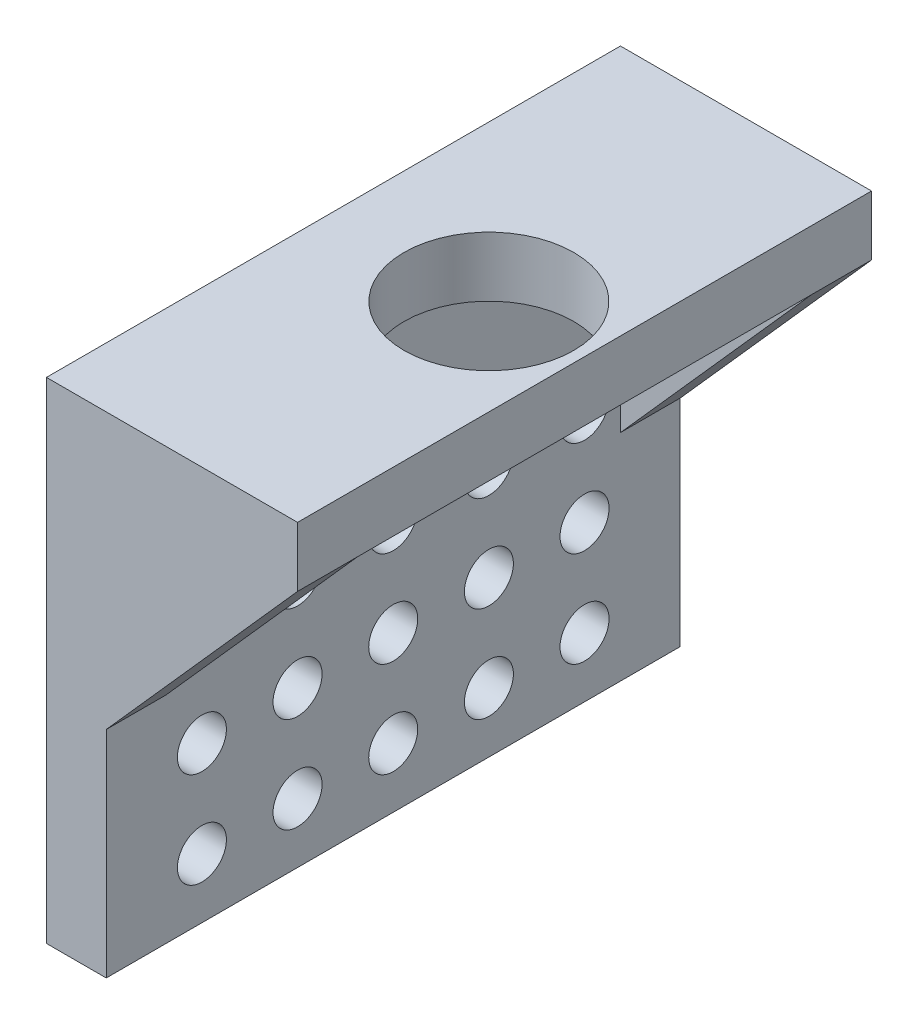
SolidWorks part; units mm, degrees
material "PMMA"
ref_plane "Front Plane" through (0, 0, 0) normal (0, 0, 1) x (1, 0, 0)
ref_plane "Top Plane" through (0, 0, 0) normal (0, 1, 0) x (1, 0, 0)
ref_plane "Right Plane" through (0, 0, 0) normal (1, 0, 0) x (0, 0, -1)
sketch "Sketch1" plane through (0, 0, 0) normal (0, 1, 0) x (1, 0, 0)
  line L0 (0, 0) -> (21, 0)
  line L1 (21, 0) -> (21, -48)
  line L2 (21, -48) -> (0, -48)
  line L3 (0, -48) -> (0, 0)
  line L4 (5, 8.2865) -> (5, -55.9573) construction
  circle A0 centre (13, -24) radius 7.1
  dimension "D6" = 14.2
  dimension "D1" = 21
  dimension "D2" = 48
  dimension "D3" = 16
  dimension "D4" = 8
  dimension "D5" = 24
extrude "Boss-Extrude1" add sketch "Sketch1" along normal blind 5
sketch "Sketch2" plane through (0, 0, 0) normal (0, -1, 0) x (1, 0, 0)
  line L0 (0, 48) -> (5, 48)
  line L1 (5, 48) -> (5, 0)
  line L2 (21, 0) -> (0, 0) construction
  line L3 (5, 0) -> (0, 0)
  line L4 (0, 0) -> (0, 48)
  dimension "D1" = 5
extrude "Boss-Extrude2" add sketch "Sketch2" along normal blind 36
sketch "Sketch4" plane through (0, 0, 0) normal (0, -1, 0) x (1, 0, 0)
  line L0 (5, 48) -> (21, 48)
  line L1 (21, 48) -> (21, 43)
  line L2 (21, 48) -> (21, 0) construction
  line L3 (21, 43) -> (5, 43)
  line L4 (5, 0) -> (5, 48) construction
  line L5 (5, 43) -> (5, 48)
  line L6 (0, 24) -> (28.1978, 24) construction
  line L7 (0, 48) -> (0, 0) construction
  line L8 (21, 5) -> (5, 5)
  line L9 (21, 0) -> (21, 5)
  line L10 (5, 0) -> (21, 0)
  line L11 (5, 5) -> (5, 0)
  dimension "D1" = 5
extrude "Boss-Extrude3" add sketch "Sketch4" along normal blind 18
sketch "Sketch5" plane through (0, 0, 48) normal (0, 0, 1) x (1, 0, 0)
  line L0 (21, 0) -> (5, -18)
  line L1 (5, -18) -> (21, -18)
  line L2 (21, -18) -> (21, 0)
extrude "Cut-Extrude1" cut sketch "Sketch5" against normal through all
sketch "Sketch6" plane through (0, 0, 0) normal (-1, 0, 0) x (0, 0, 1)
  line L0 (24, 5) -> (24, -39.1174) construction
  line L1 (0, 5) -> (48, 5) construction
  line L2 (48, -36) -> (0, -36) construction
  circle A0 centre (8, -31) radius 2.05
  circle A1 centre (16, -31) radius 2.05
  circle A2 centre (24, -31) radius 2.05
  circle A3 centre (32, -31) radius 2.05
  circle A4 centre (40, -31) radius 2.05
  circle A5 centre (16, -23) radius 2.05
  circle A6 centre (24, -23) radius 2.05
  circle A7 centre (32, -23) radius 2.05
  circle A8 centre (40, -23) radius 2.05
  circle A9 centre (16, -15) radius 2.05
  circle A10 centre (24, -15) radius 2.05
  circle A11 centre (32, -15) radius 2.05
  circle A12 centre (40, -15) radius 2.05
  circle A13 centre (8, -23) radius 2.05
  circle A14 centre (8, -15) radius 2.05
  dimension "D1" = 4.1
  dimension "D2" = 16
  dimension "D3" = 5
  dimension "D6" = 16
  dimension "D7" = 32
  dimension "D4" = 5
  dimension "D5" = 3
extrude "Cut-Extrude2" cut sketch "Sketch6" against normal blind 18
